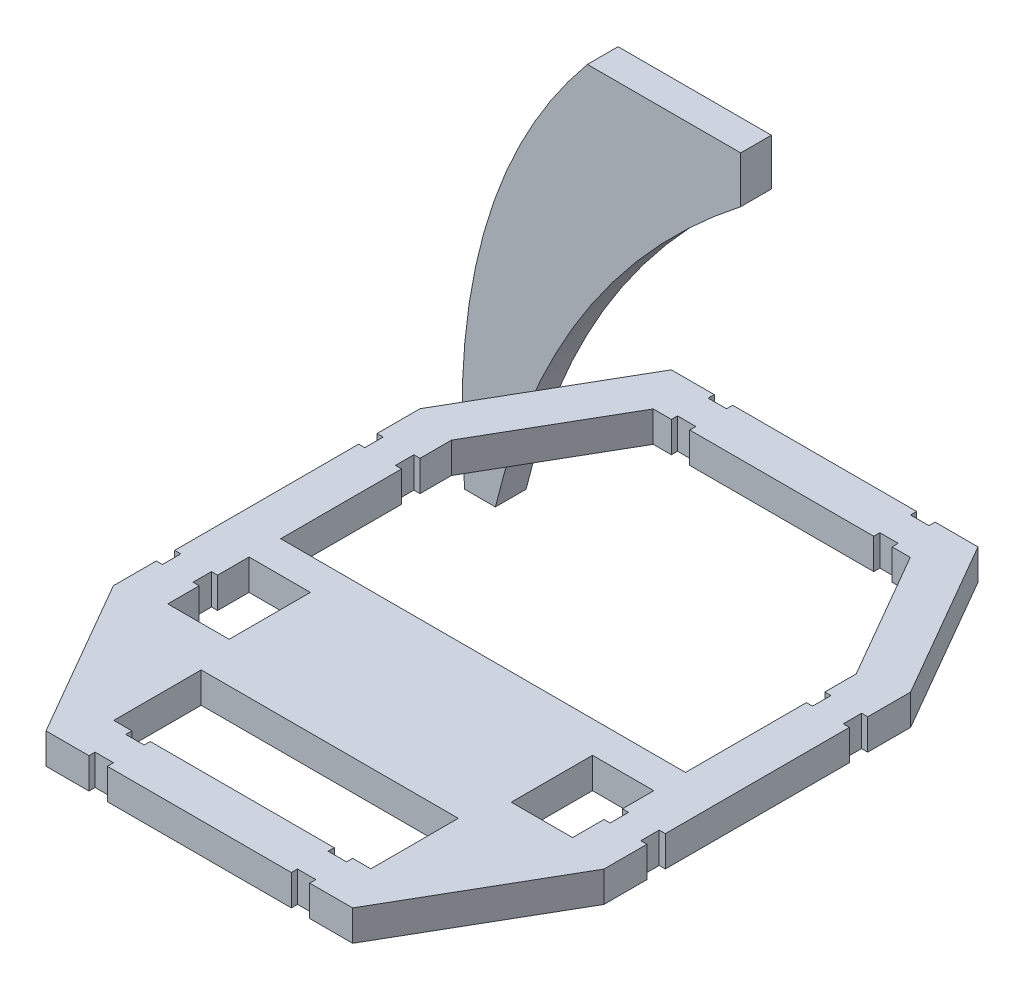
SolidWorks part; units mm, degrees
ref_plane "Plan de face" through (0, 0, 0) normal (0, 0, 1) x (1, 0, 0)
ref_plane "Plan de dessus" through (0, 0, 0) normal (0, 1, 0) x (1, 0, 0)
ref_plane "Plan de droite" through (0, 0, 0) normal (1, 0, 0) x (0, 0, -1)
sketch "Esquisse1" plane through (0, 0, 0) normal (0, 0, 1) x (1, 0, 0)
  line L0 (-89.3953, 0) -> (-64.3953, 0)
  line L1 (-64.3953, 0) -> (-64.3953, -7.6)
  line L2 (-109.3953, -70) -> (-104.3953, -70)
  spline S0 degree 2 poles (-89.3953, 0) (-112.8926, -28.4442) (-109.3953, -70) knots 0 0 0 1 1 1
  spline S1 degree 2 poles (-104.3953, -70) (-95.305, -31.7455) (-64.3953, -7.6) knots 0 0 0 1 1 1
extrude "Foot" add sketch "Esquisse1" along normal blind 5
sketch "Feet base" plane through (0, 0, 0) normal (0, 1, 0) x (1, 0, 0)
  line L0 (-275.9159, -82.8503) -> (-268.9159, -82.8503)
  line L1 (-268.9159, -82.8503) -> (-268.9159, -81.8503)
  line L2 (-268.9159, -81.8503) -> (-265.9159, -81.8503)
  line L3 (-265.9159, -81.8503) -> (-265.9159, -82.8503)
  line L4 (-265.9159, -82.8503) -> (-235.9159, -82.8503)
  line L5 (-235.9159, -82.8503) -> (-235.9159, -81.8503)
  line L6 (-235.9159, -81.8503) -> (-232.9159, -81.8503)
  line L7 (-232.9159, -81.8503) -> (-232.9159, -82.8503)
  line L8 (-232.9159, -82.8503) -> (-225.9159, -82.8503)
  line L9 (-225.9159, -82.8503) -> (-210.9159, -56.8696)
  line L10 (-225.9159, 19.1112) -> (-232.9159, 19.1112)
  line L11 (-232.9159, 19.1112) -> (-232.9159, 18.1112)
  line L12 (-232.9159, 18.1112) -> (-235.9159, 18.1112)
  line L13 (-235.9159, 18.1112) -> (-235.9159, 19.1112)
  line L14 (-235.9159, 19.1112) -> (-265.9159, 19.1112)
  line L15 (-265.9159, 19.1112) -> (-265.9159, 18.1112)
  line L16 (-265.9159, 18.1112) -> (-268.9159, 18.1112)
  line L17 (-268.9159, 18.1112) -> (-268.9159, 19.1112)
  line L18 (-268.9159, 19.1112) -> (-275.9159, 19.1112)
  line L19 (-275.9159, 19.1112) -> (-290.9159, -6.8696)
  line L20 (-283.9159, -49.8696) -> (-283.9159, -54.9939)
  line L21 (-283.9159, -8.7452) -> (-283.9159, -13.8696)
  line L22 (-284.9159, -49.8696) -> (-283.9159, -49.8696)
  line L23 (-284.9159, -46.8696) -> (-284.9159, -49.8696)
  line L24 (-283.9159, -46.8696) -> (-284.9159, -46.8696)
  line L25 (-283.9159, -16.8696) -> (-283.9159, -46.8696)
  line L26 (-284.9159, -16.8696) -> (-283.9159, -16.8696)
  line L27 (-284.9159, -13.8696) -> (-284.9159, -16.8696)
  line L28 (-283.9159, -13.8696) -> (-284.9159, -13.8696)
  line L29 (-283.9159, -54.9939) -> (-271.8745, -75.8503)
  line L30 (-210.9159, -56.8696) -> (-210.9159, -49.8696)
  line L31 (-210.9159, -49.8696) -> (-211.9159, -49.8696)
  line L32 (-211.9159, -49.8696) -> (-211.9159, -46.8696)
  line L33 (-211.9159, -46.8696) -> (-210.9159, -46.8696)
  line L34 (-210.9159, -46.8696) -> (-210.9159, -16.8696)
  line L35 (-210.9159, -16.8696) -> (-211.9159, -16.8696)
  line L36 (-211.9159, -16.8696) -> (-211.9159, -13.8696)
  line L37 (-211.9159, -13.8696) -> (-210.9159, -13.8696)
  line L38 (-210.9159, -13.8696) -> (-210.9159, -6.8696)
  line L39 (-210.9159, -6.8696) -> (-225.9159, 19.1112)
  line L40 (-268.9159, 12.1112) -> (-271.8745, 12.1112)
  line L41 (-229.9574, 12.1112) -> (-232.9159, 12.1112)
  line L42 (-268.9159, 13.1112) -> (-268.9159, 12.1112)
  line L43 (-265.9159, 13.1112) -> (-268.9159, 13.1112)
  line L44 (-265.9159, 12.1112) -> (-265.9159, 13.1112)
  line L45 (-235.9159, 12.1112) -> (-265.9159, 12.1112)
  line L46 (-235.9159, 13.1112) -> (-235.9159, 12.1112)
  line L47 (-232.9159, 13.1112) -> (-235.9159, 13.1112)
  line L48 (-232.9159, 12.1112) -> (-232.9159, 13.1112)
  line L49 (-271.8745, 12.1112) -> (-283.9159, -8.7452)
  line L50 (-290.9159, -6.8696) -> (-290.9159, -13.8696)
  line L51 (-290.9159, -13.8696) -> (-289.9159, -13.8696)
  line L52 (-289.9159, -13.8696) -> (-289.9159, -16.8696)
  line L53 (-289.9159, -16.8696) -> (-290.9159, -16.8696)
  line L54 (-290.9159, -16.8696) -> (-290.9159, -46.8696)
  line L55 (-290.9159, -46.8696) -> (-289.9159, -46.8696)
  line L56 (-289.9159, -46.8696) -> (-289.9159, -49.8696)
  line L57 (-289.9159, -49.8696) -> (-290.9159, -49.8696)
  line L58 (-290.9159, -49.8696) -> (-290.9159, -56.8696)
  line L59 (-290.9159, -56.8696) -> (-275.9159, -82.8503)
  line L70 (-217.9159, -13.8696) -> (-217.9159, -8.7452)
  line L71 (-217.9159, -54.9939) -> (-217.9159, -49.8696)
  line L72 (-216.9159, -13.8696) -> (-217.9159, -13.8696)
  line L73 (-216.9159, -16.8696) -> (-216.9159, -13.8696)
  line L74 (-217.9159, -16.8696) -> (-216.9159, -16.8696)
  line L75 (-217.9159, -46.8696) -> (-217.9159, -16.8696)
  line L76 (-216.9159, -46.8696) -> (-217.9159, -46.8696)
  line L77 (-216.9159, -49.8696) -> (-216.9159, -46.8696)
  line L78 (-217.9159, -49.8696) -> (-216.9159, -49.8696)
  line L79 (-217.9159, -8.7452) -> (-229.9574, 12.1112)
  line L80 (-232.9159, -75.8503) -> (-229.9574, -75.8503)
  line L81 (-271.8745, -75.8503) -> (-268.9159, -75.8503)
  line L82 (-232.9159, -76.8503) -> (-232.9159, -75.8503)
  line L83 (-235.9159, -76.8503) -> (-232.9159, -76.8503)
  line L84 (-235.9159, -75.8503) -> (-235.9159, -76.8503)
  line L85 (-265.9159, -75.8503) -> (-235.9159, -75.8503)
  line L86 (-265.9159, -76.8503) -> (-265.9159, -75.8503)
  line L87 (-268.9159, -76.8503) -> (-265.9159, -76.8503)
  line L88 (-268.9159, -75.8503) -> (-268.9159, -76.8503)
  line L89 (-229.9574, -75.8503) -> (-217.9159, -54.9939)
  dimension "D1" = 50
  dimension "D2" = 30
  dimension "D3" = 7
  dimension "D4" = 3
  dimension "D5" = 5
  dimension "D8" = 7
  dimension "D6" = 7
  dimension "D9" = 7
  dimension "D10" = 7
  dimension "D11" = 7
  dimension "D12" = 7
sketch "Feet base w/ battery" plane through (0, 0, 0) normal (0, 1, 0) x (1, 0, 0)
  line L0 (-34.4216, -148.2482) -> (-27.4216, -148.2482)
  line L1 (-27.4216, -148.2482) -> (-27.4216, -147.2482)
  line L2 (-27.4216, -147.2482) -> (-24.4216, -147.2482)
  line L3 (-24.4216, -147.2482) -> (-24.4216, -148.2482)
  line L4 (-24.4216, -148.2482) -> (5.5784, -148.2482)
  line L5 (5.5784, -148.2482) -> (5.5784, -147.2482)
  line L6 (5.5784, -147.2482) -> (8.5784, -147.2482)
  line L7 (8.5784, -147.2482) -> (8.5784, -148.2482)
  line L8 (8.5784, -148.2482) -> (15.5784, -148.2482)
  line L9 (15.5784, -148.2482) -> (30.5784, -122.2674)
  line L10 (15.5784, -46.2867) -> (8.5784, -46.2867)
  line L11 (8.5784, -46.2867) -> (8.5784, -47.2867)
  line L12 (8.5784, -47.2867) -> (5.5784, -47.2867)
  line L13 (5.5784, -47.2867) -> (5.5784, -46.2867)
  line L14 (5.5784, -46.2867) -> (-24.4216, -46.2867)
  line L15 (-24.4216, -46.2867) -> (-24.4216, -47.2867)
  line L16 (-24.4216, -47.2867) -> (-27.4216, -47.2867)
  line L17 (-27.4216, -47.2867) -> (-27.4216, -46.2867)
  line L18 (-27.4216, -46.2867) -> (-34.4216, -46.2867)
  line L19 (-34.4216, -46.2867) -> (-49.4216, -72.2674)
  line L20 (-42.4216, -115.2674) -> (-42.4216, -120.3918)
  line L21 (-42.4216, -74.1431) -> (-42.4216, -79.2674)
  line L22 (-43.4216, -115.2674) -> (-42.4216, -115.2674)
  line L23 (-43.4216, -112.2674) -> (-43.4216, -115.2674)
  line L24 (-42.4216, -112.2674) -> (-43.4216, -112.2674)
  line L26 (-43.4216, -82.2674) -> (-42.4216, -82.2674)
  line L27 (-43.4216, -79.2674) -> (-43.4216, -82.2674)
  line L28 (-42.4216, -79.2674) -> (-43.4216, -79.2674)
  line L29 (23.5784, -82.2674) -> (23.5784, -101.9846)
  line L30 (30.5784, -122.2674) -> (30.5784, -115.2674)
  line L31 (30.5784, -115.2674) -> (29.5784, -115.2674)
  line L32 (29.5784, -115.2674) -> (29.5784, -112.2674)
  line L33 (29.5784, -112.2674) -> (30.5784, -112.2674)
  line L34 (30.5784, -112.2674) -> (30.5784, -82.2674)
  line L35 (30.5784, -82.2674) -> (29.5784, -82.2674)
  line L36 (29.5784, -82.2674) -> (29.5784, -79.2674)
  line L37 (29.5784, -79.2674) -> (30.5784, -79.2674)
  line L38 (30.5784, -79.2674) -> (30.5784, -72.2674)
  line L39 (30.5784, -72.2674) -> (15.5784, -46.2867)
  line L40 (-27.4216, -53.2867) -> (-30.3802, -53.2867)
  line L41 (11.5369, -53.2867) -> (8.5784, -53.2867)
  line L42 (-27.4216, -52.2867) -> (-27.4216, -53.2867)
  line L43 (-24.4216, -52.2867) -> (-27.4216, -52.2867)
  line L44 (-24.4216, -53.2867) -> (-24.4216, -52.2867)
  line L45 (5.5784, -53.2867) -> (-24.4216, -53.2867)
  line L46 (5.5784, -52.2867) -> (5.5784, -53.2867)
  line L47 (8.5784, -52.2867) -> (5.5784, -52.2867)
  line L48 (8.5784, -53.2867) -> (8.5784, -52.2867)
  line L49 (-30.3802, -53.2867) -> (-42.4216, -74.1431)
  line L50 (-49.4216, -72.2674) -> (-49.4216, -79.2674)
  line L51 (-49.4216, -79.2674) -> (-48.4216, -79.2674)
  line L52 (-48.4216, -79.2674) -> (-48.4216, -82.2674)
  line L53 (-48.4216, -82.2674) -> (-49.4216, -82.2674)
  line L54 (-49.4216, -82.2674) -> (-49.4216, -112.2674)
  line L55 (-49.4216, -112.2674) -> (-48.4216, -112.2674)
  line L56 (-48.4216, -112.2674) -> (-48.4216, -115.2674)
  line L57 (-48.4216, -115.2674) -> (-49.4216, -115.2674)
  line L58 (-49.4216, -115.2674) -> (-49.4216, -122.2674)
  line L59 (-49.4216, -122.2674) -> (-34.4216, -148.2482)
  line L60 (23.5784, -79.2674) -> (23.5784, -74.1431)
  line L61 (23.5784, -120.3918) -> (23.5784, -115.2674)
  line L62 (24.5784, -79.2674) -> (23.5784, -79.2674)
  line L63 (24.5784, -82.2674) -> (24.5784, -79.2674)
  line L64 (23.5784, -82.2674) -> (24.5784, -82.2674)
  line L65 (-42.4216, -82.2674) -> (-42.4216, -101.9846)
  line L66 (24.5784, -112.2674) -> (23.5784, -112.2674)
  line L67 (24.5784, -115.2674) -> (24.5784, -112.2674)
  line L68 (23.5784, -115.2674) -> (24.5784, -115.2674)
  line L69 (23.5784, -74.1431) -> (11.5369, -53.2867)
  line L70 (8.5784, -141.2482) -> (11.5369, -141.2482)
  line L71 (-30.3802, -141.2482) -> (-27.4216, -141.2482)
  line L72 (8.5784, -142.2482) -> (8.5784, -141.2482)
  line L73 (5.5784, -142.2482) -> (8.5784, -142.2482)
  line L74 (5.5784, -141.2482) -> (5.5784, -142.2482)
  line L75 (-24.4216, -141.2482) -> (5.5784, -141.2482)
  line L76 (-24.4216, -142.2482) -> (-24.4216, -141.2482)
  line L77 (-27.4216, -142.2482) -> (-24.4216, -142.2482)
  line L78 (-27.4216, -141.2482) -> (-27.4216, -142.2482)
  line L79 (23.5784, -107.1431) -> (23.5784, -112.2674)
  line L80 (-42.4216, -101.9846) -> (23.5784, -101.9846)
  line L81 (11.5369, -126.9846) -> (-30.3802, -126.9846)
  line L82 (-42.4216, -107.1431) -> (-32.4216, -107.1431)
  line L83 (-32.4216, -107.1431) -> (-32.4216, -120.3918)
  line L84 (-32.4216, -120.3918) -> (-42.4216, -120.3918)
  line L85 (13.5784, -107.1431) -> (23.5784, -107.1431)
  line L86 (13.5784, -107.1431) -> (13.5784, -120.3918)
  line L87 (23.5784, -120.3918) -> (13.5784, -120.3918)
  line L88 (11.5369, -141.2482) -> (11.5369, -126.9846)
  line L89 (-30.3802, -141.2482) -> (-30.3802, -126.9846)
  line L90 (-42.4216, -112.2674) -> (-42.4216, -107.1431)
  dimension "D1" = 25
  dimension "D2" = 10
  dimension "D3" = 5.1244
  dimension "D4" = 10
extrude "Feet base w/battery holder" add sketch "Feet base w/ battery" along normal blind 5 separate body
